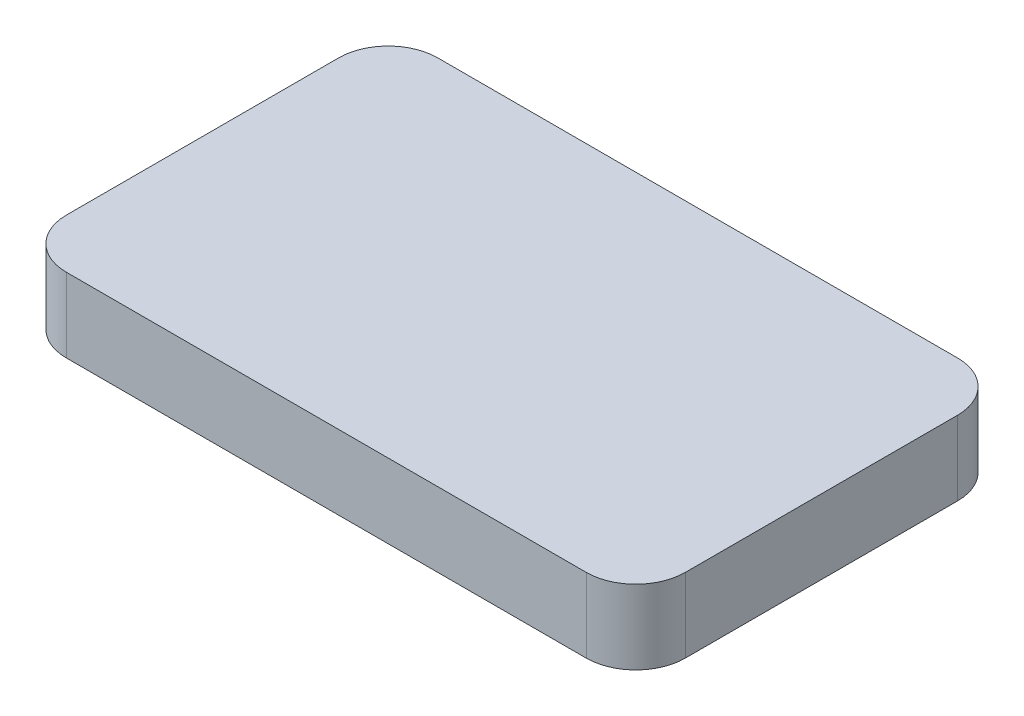
SolidWorks part; units mm, degrees
ref_plane "Front Plane" through (0, 0, 0) normal (0, 0, 1) x (1, 0, 0)
ref_plane "Top Plane" through (0, 0, 0) normal (0, 1, 0) x (1, 0, 0)
ref_plane "Right Plane" through (0, 0, 0) normal (1, 0, 0) x (0, 0, -1)
sketch "Sketch2" plane through (0, 0, 0) normal (0, 1, 0) x (1, 0, 0)
  line L1 (-12.5, -7.5) -> (12.5, -7.5)
  line L2 (-12.5, -7.5) -> (-12.5, 7.5)
  line L3 (-12.5, 7.5) -> (12.5, 7.5)
  line L4 (12.5, -7.5) -> (12.5, 7.5)
  line L5 (-12.5, -7.5) -> (12.5, 7.5) construction
  line L6 (-12.5, 7.5) -> (12.5, -7.5) construction
  point P0 (0, 0)
  dimension "D1" = 25
  dimension "D2" = 15
extrude "Boss-Extrude1" add sketch "Sketch2" along normal blind 3
fillet "Fillet1" radius 2 4 edges at (-12.5, 1.5, -7.5) (-12.5, 1.5, 7.5) (12.5, 1.5, -7.5) (12.5, 1.5, 7.5)
